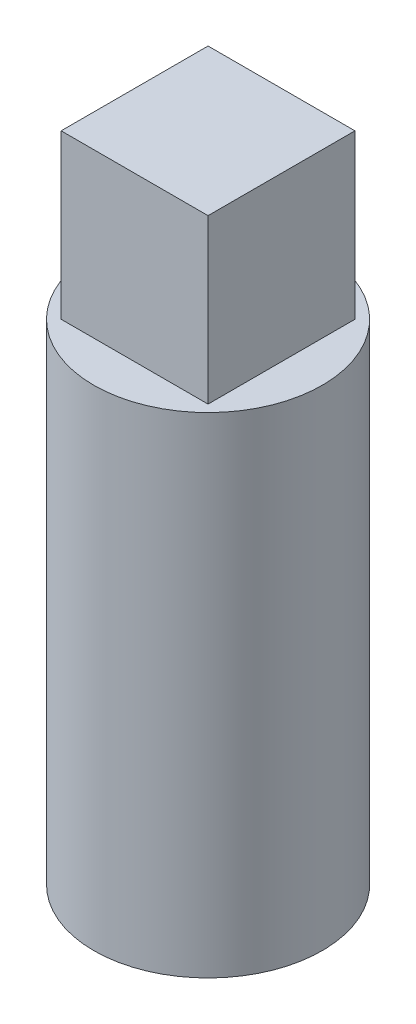
SolidWorks part; units mm, degrees
ref_plane "Front Plane" through (0, 0, 0) normal (0, 0, 1) x (1, 0, 0)
ref_plane "Top Plane" through (0, 0, 0) normal (0, 1, 0) x (1, 0, 0)
ref_plane "Right Plane" through (0, 0, 0) normal (1, 0, 0) x (0, 0, -1)
sketch "Sketch1" plane through (0, 0, 0) normal (0, 1, 0) x (1, 0, 0)
  circle A0 centre (0, 0) radius 1.4
extrude "Boss-Extrude1" add sketch "Sketch1" along normal blind 6 contours A0
sketch "Sketch2" plane through (0, 6, 0) normal (0, 1, 0) x (1, 0, 0)
  line L0 (0, 0) -> (0, 0.9)
  line L1 (0, 0) -> (0.9, 0)
  line L2 (0, 0) -> (0, -0.9)
  line L3 (0, 0) -> (-0.9, 0)
  line L4 (0, 0.9) -> (-0.9, 0.9)
  line L5 (-0.9, 0.9) -> (-0.9, 0)
  line L6 (-0.9, -0.9) -> (-0.9, 0)
  line L7 (0, -0.9) -> (-0.9, -0.9)
  line L8 (0, 0.9) -> (0.9, 0.9)
  line L9 (0.9, 0.9) -> (0.9, 0)
  line L10 (0, -0.9) -> (0.9, -0.9)
  line L11 (0.9, -0.9) -> (0.9, 0)
extrude "Boss-Extrude2" add sketch "Sketch2" along normal blind 2 contours L4 L5 L3 L0 | L7 L2 L3 L6 | L9 L8 L0 L1 | L10 L11 L1 L2
